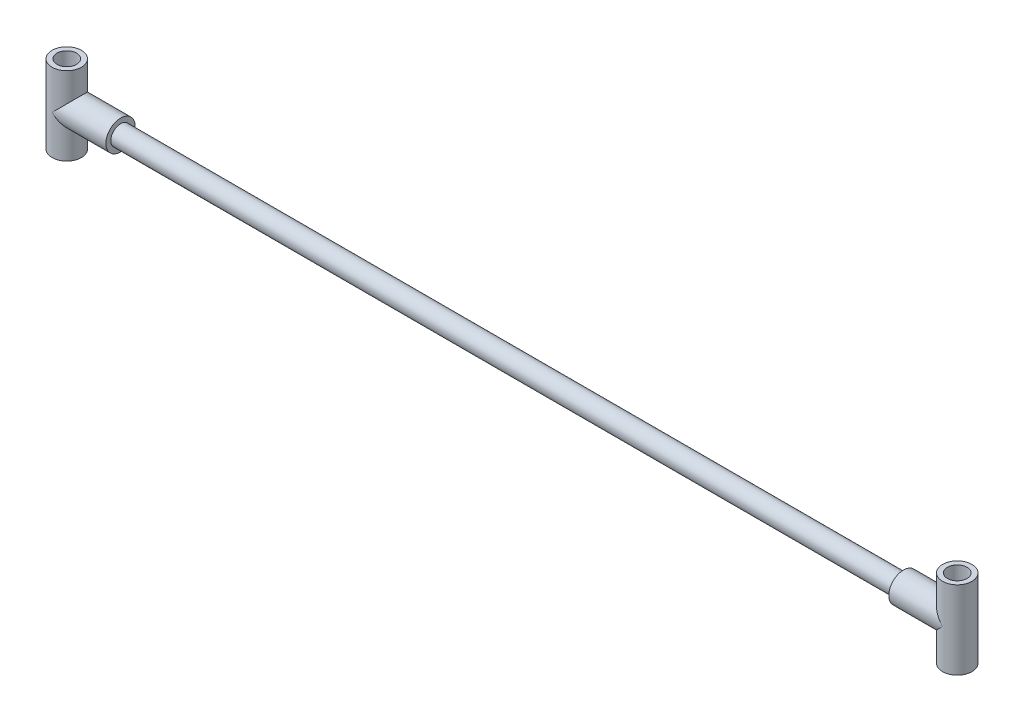
SolidWorks part; units mm, degrees
ref_plane "Front Plane" through (0, 0, 0) normal (0, 0, 1) x (1, 0, 0)
ref_plane "Top Plane" through (0, 0, 0) normal (0, 1, 0) x (1, 0, 0)
ref_plane "Right Plane" through (0, 0, 0) normal (1, 0, 0) x (0, 0, -1)
sketch "Sketch1" plane through (0, 0, 0) normal (1, 0, 0) x (0, 0, -1)
  circle A0 centre (0, 0) radius 5
  dimension "D1" = 10
extrude "Boss-Extrude1" add sketch "Sketch1" along normal mid plane 400
sketch "Sketch2" plane through (0, 0, 0) normal (0, 1, 0) x (1, 0, 0)
  line L0 (200, -5) -> (200, 5) construction
  line L1 (0, 0) -> (0, -75.3612) construction
  circle A0 centre (227.5, 0) radius 7.5
  circle A1 centre (-227.5, 0) radius 7.5
  dimension "D1" = 15
  dimension "D2" = 27.5
extrude "Boss-Extrude2" add sketch "Sketch2" along normal mid plane 40 separate body
sketch "Sketch3" plane through (-200, 0, 0) normal (-1, 0, 0) x (0, 0, 1)
  circle A0 centre (0, 0) radius 7.5
  dimension "D1" = 15
extrude "Boss-Extrude3" add sketch "Sketch3" along normal blind 27.5
sketch "Sketch4" plane through (200, 0, 0) normal (1, 0, 0) x (0, 0, -1)
  circle A0 centre (0, 0) radius 7.5
  dimension "D1" = 15
extrude "Boss-Extrude4" add sketch "Sketch4" along normal blind 27.5
sketch "Sketch5" plane through (0, 20, 0) normal (0, 1, 0) x (1, 0, 0)
  line L0 (0, 0) -> (0, -70.6314) construction
  circle A0 centre (227.5, 0) radius 5
  circle A1 centre (-227.5, 0) radius 5
  dimension "D1" = 10
extrude "Cut-Extrude1" cut sketch "Sketch5" against normal through all
